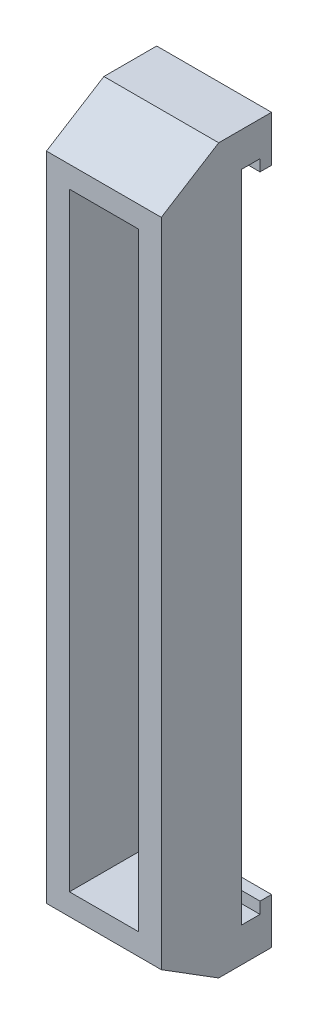
SolidWorks part; units mm, degrees
ref_plane "Płaszczyzna przednia" through (0, 0, 0) normal (0, 0, 1) x (1, 0, 0)
ref_plane "Płaszczyzna górna" through (0, 0, 0) normal (0, 1, 0) x (1, 0, 0)
ref_plane "Płaszczyzna prawa" through (0, 0, 0) normal (1, 0, 0) x (0, 0, -1)
sketch "Szkic3" plane through (0, 0, 0) normal (0, 0, 1) x (1, 0, 0)
  line L1 (0, 0) -> (10, 0)
  line L2 (0, 0) -> (0, 63)
  line L3 (0, 63) -> (10, 63)
  line L4 (10, 0) -> (10, 63)
  point P5 (0, 0)
  point P6 (0, 0)
extrude "Dodanie-wyciągnięcie1" add sketch "Szkic3" along normal blind 7
sketch "Szkic4" plane through (0, 0, 7) normal (0, 0, 1) x (1, 0, 0)
  line L1 (2, 5) -> (8, 5)
  line L2 (2, 5) -> (2, 58)
  line L3 (2, 58) -> (8, 58)
  line L4 (8, 5) -> (8, 58)
  point P4 (0, 0)
  point P5 (0, 0)
  point P6 (0, 0)
  point P7 (0, 0)
extrude "Wytnij-wyciągnięcie1" cut sketch "Szkic4" against normal up to next
chamfer "Sfazowanie1" distance 5 angle 32 2 edges at (5, 0, 7) (5, 63, 7)
sketch "Szkic6" plane through (0, 0, 0) normal (-1, 0, 0) x (0, 0, 1)
  line L0 (0, 63) -> (-2.6, 63)
  line L1 (-2.6, 63) -> (-2.6, 59)
  line L2 (-2.6, 59) -> (-1.6, 59)
  line L3 (-1.6, 59) -> (-1.6, 60)
  line L4 (-1.6, 60) -> (0, 60)
  line L5 (0, 63) -> (0, 0) construction
  line L6 (0, 60) -> (0, 63)
  line L7 (0, 0) -> (-2.6, 0)
  line L8 (-2.6, 0) -> (-2.6, 4)
  line L9 (-2.6, 4) -> (-1.6, 4)
  line L10 (-1.6, 4) -> (-1.6, 3)
  line L11 (-1.6, 3) -> (0, 3)
  line L12 (0, 3) -> (0, 0)
  point P13 (0, 0)
  point P18 (0, 0)
  point P19 (0, 0)
  point P20 (0, 0)
  point P21 (0, 0)
  point P22 (0, 0)
  point P23 (0, 0)
  point P24 (0, 0)
  point P25 (0, 0)
  point P26 (0, 0)
  point P27 (0, 0)
  point P28 (0, 0)
  point P29 (0, 0)
  point P30 (0, 0)
  point P31 (0, 0)
extrude "Dodanie-wyciągnięcie2" add sketch "Szkic6" against normal blind 10
